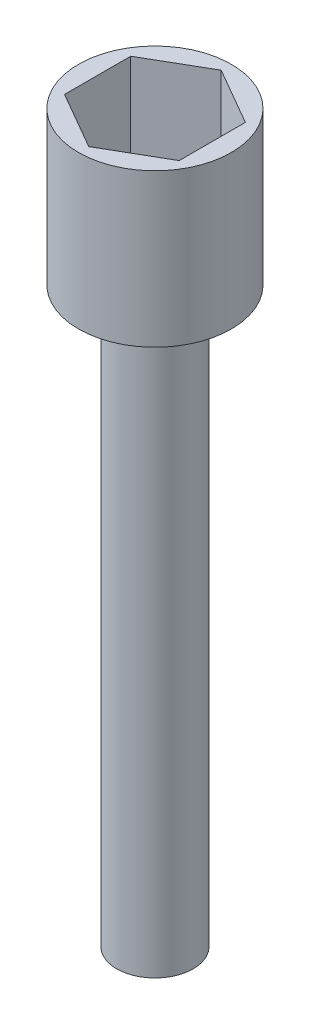
SolidWorks part; units mm, degrees
ref_plane "Plan de face" through (0, 0, 0) normal (0, 0, 1) x (1, 0, 0)
ref_plane "Plan de dessus" through (0, 0, 0) normal (0, 1, 0) x (1, 0, 0)
ref_plane "Plan de droite" through (0, 0, 0) normal (1, 0, 0) x (0, 0, -1)
sketch "Esquisse1" plane through (0, 0, 0) normal (0, 1, 0) x (1, 0, 0)
  circle A0 centre (0, 0) radius 1
extrude "Boss.-Extru.1" add sketch "Esquisse1" along normal blind 15
sketch "Esquisse2" plane through (0, 15, 0) normal (0, 1, 0) x (1, 0, 0)
  circle A0 centre (0, 0) radius 2
extrude "Boss.-Extru.2" add sketch "Esquisse2" along normal blind 4
sketch "Esquisse3" plane through (0, 19, 0) normal (0, 1, 0) x (1, 0, 0)
  line L1 (0, 1.7321) -> (-1.5, 0.866)
  line L2 (-1.5, 0.866) -> (-1.5, -0.866)
  line L3 (-1.5, -0.866) -> (0, -1.7321)
  line L4 (0, -1.7321) -> (1.5, -0.866)
  line L5 (1.5, -0.866) -> (1.5, 0.866)
  line L6 (1.5, 0.866) -> (0, 1.7321)
  circle A0 centre (0, 0) radius 1.5 construction
extrude "Enlèv. mat.-Extru.1" cut sketch "Esquisse3" against normal blind 3
